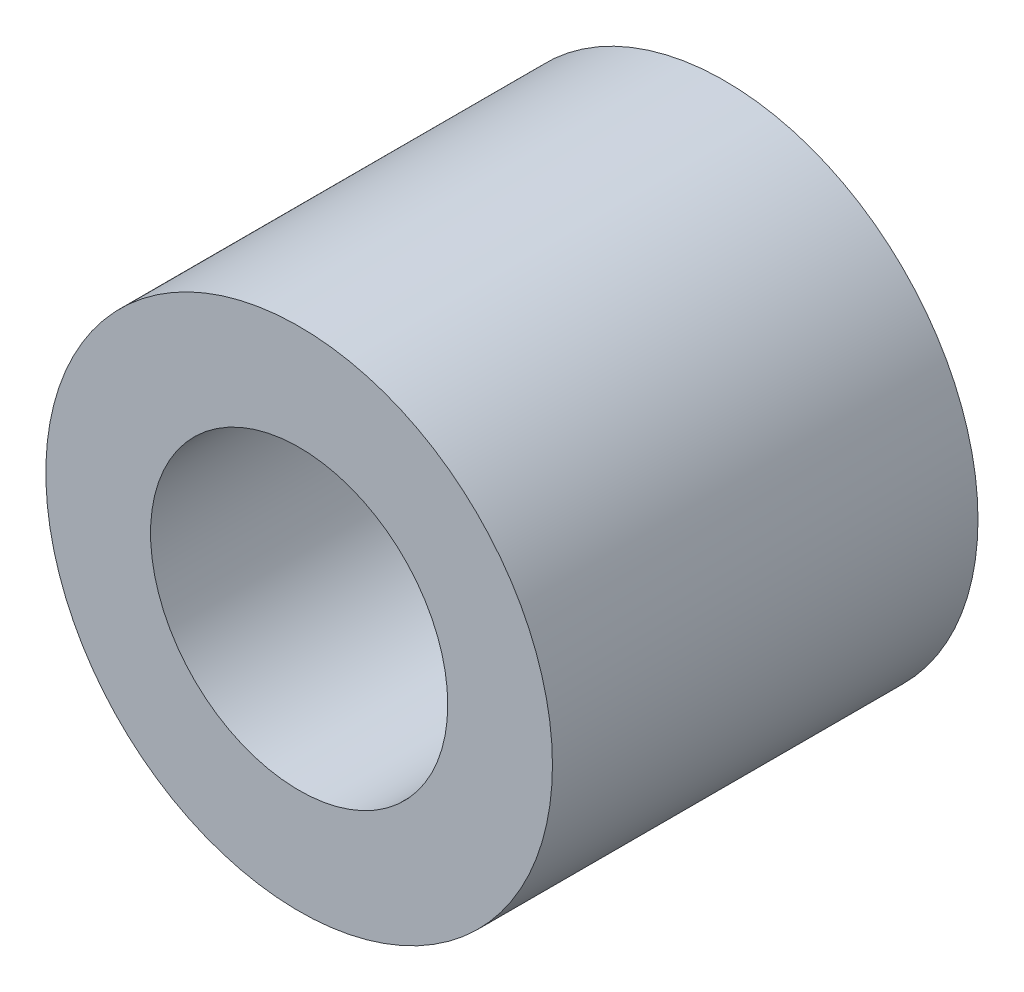
SolidWorks part; units mm, degrees
material "ABS PC"
ref_plane "Front Plane" through (0, 0, 0) normal (0, 0, 1) x (1, 0, 0)
ref_plane "Top Plane" through (0, 0, 0) normal (0, 1, 0) x (1, 0, 0)
ref_plane "Right Plane" through (0, 0, 0) normal (1, 0, 0) x (0, 0, -1)
sketch "Sketch1" plane through (0, 0, 0) normal (0, 0, 1) x (1, 0, 0)
  circle A0 centre (0, 0) radius 2.794
  circle A1 centre (0, 0) radius 4.7625
  dimension "D1" = 9.525
  dimension "D2" = 5.588
extrude "Boss-Extrude1" add sketch "Sketch1" along normal blind 8.001
